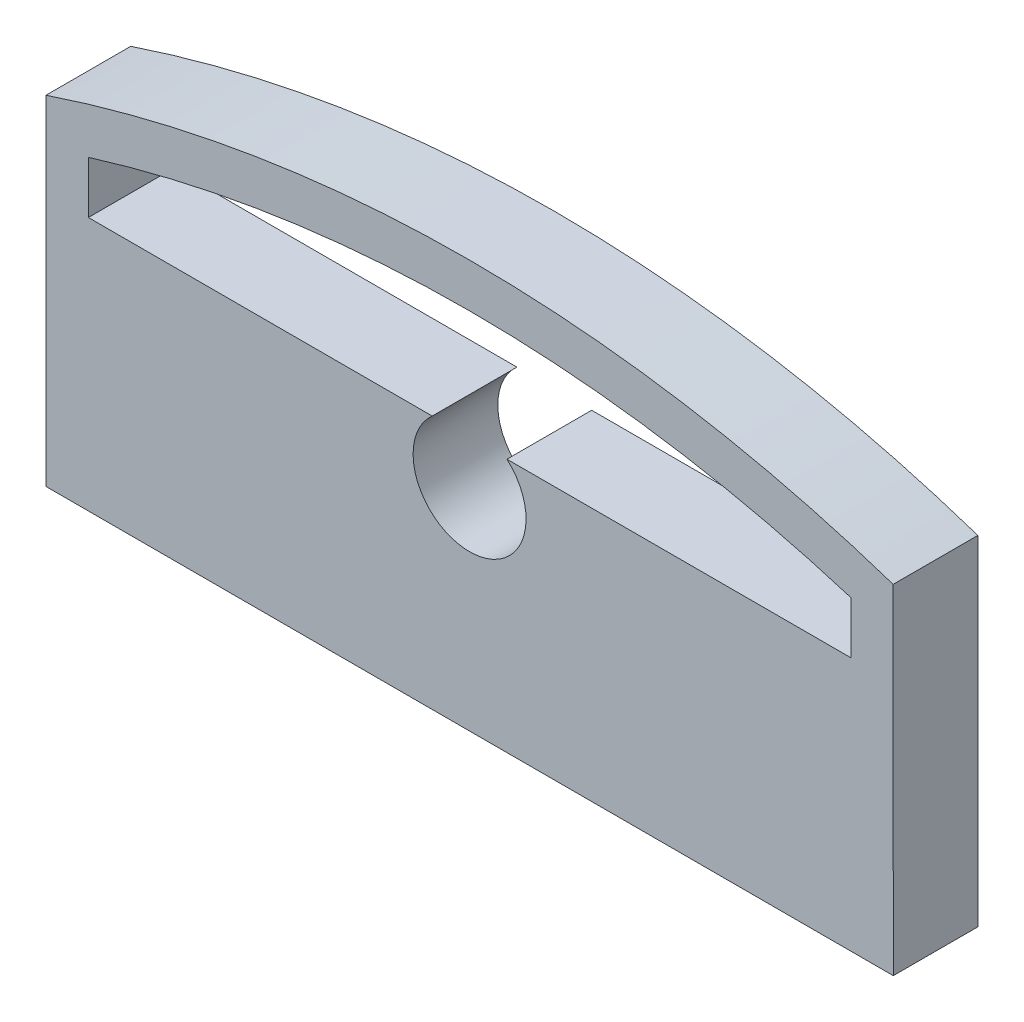
SolidWorks part; units mm, degrees
ref_plane "Front Plane" through (0, 0, 0) normal (0, 0, 1) x (1, 0, 0)
ref_plane "Top Plane" through (0, 0, 0) normal (0, 1, 0) x (1, 0, 0)
ref_plane "Right Plane" through (0, 0, 0) normal (1, 0, 0) x (0, 0, -1)
sketch "Sketch2" plane through (0, 0, 0) normal (0, 0, 1) x (1, 0, 0)
  circle A0 centre (0, 0) radius 95
  circle A1 centre (0, 0) radius 75
  dimension "D1" = 190
  dimension "D2" = 150
  dimension "D3" = 20
extrude "Boss-Extrude1" add sketch "Sketch2" along normal blind 5
sketch "Sketch3" plane through (0, 0, 0) normal (0, 0, 1) x (1, 0, 0)
  circle A0 centre (0, 0) radius 87
  circle A1 centre (0, 0) radius 95 construction
  circle A2 centre (0, 0) radius 84
  dimension "D1" = 8
  dimension "D2" = 3
extrude "Boss-Extrude2" add sketch "Sketch3" along normal blind 10
sketch "Sketch4" plane through (0, 0, 5) normal (0, 0, 1) x (1, 0, 0)
  circle A0 centre (0, 0) radius 75
  circle A1 centre (0, 0) radius 78
  dimension "D1" = 3
extrude "Boss-Extrude3" add sketch "Sketch4" along normal blind 70
sketch "Sketch5" plane through (0, 0, 0) normal (0, 0, 1) x (1, 0, 0)
  line L0 (0, 102.8311) -> (0, -104.5953) construction
  line L1 (-104.5953, 0) -> (100.8148, -2.2683) construction
ref_plane "Plane1" through (10, 0, 0) normal (1, 0, 0) x (0, 0, -1)
sketch "Sketch6" plane through (10, 0, 0) normal (1, 0, 0) x (0, 0, -1)
  line L1 (-45, 46) -> (-35, 46)
  line L2 (-45, 46) -> (-45, 34)
  line L3 (-45, 34) -> (-35, 34)
  line L4 (-35, 46) -> (-35, 34)
  line L5 (-45, 46) -> (-35, 34) construction
  line L6 (-45, 34) -> (-35, 46) construction
  point P0 (-40, 40)
  dimension "D1" = 10
  dimension "D2" = 12
extrude "Cut-Extrude3" cut sketch "Sketch6" against normal through all both and the other way through all
sketch "Sketch7" plane through (10, 0, 0) normal (1, 0, 0) x (0, 0, -1)
  line L1 (-45, -34) -> (-35, -34)
  line L2 (-45, -34) -> (-45, -46)
  line L3 (-45, -46) -> (-35, -46)
  line L4 (-35, -34) -> (-35, -46)
  line L5 (-45, -34) -> (-35, -46) construction
  line L6 (-45, -46) -> (-35, -34) construction
  point P0 (-40, -40)
  dimension "D1" = 10
  dimension "D2" = 12
extrude "Cut-Extrude4" cut sketch "Sketch7" against normal through all both and the other way through all
ref_plane "Plane2" through (0, 0, -10) normal (0, 0, -1) x (-1, 0, 0)
sketch "Sketch8" plane through (0, 0, -10) normal (0, 0, -1) x (-1, 0, 0)
  line L0 (0, 75) -> (-30, 75)
  line L1 (0, 102.8311) -> (0, -104.5953) construction
  line L2 (-30, 75) -> (-30, 96)
  line L3 (0, 75) -> (30, 75)
  line L4 (30, 75) -> (30, 96)
  circle A0 centre (0, 0) radius 75 construction
  arc A1 (-30, 96) -> (30, 96) centre (0, 6.4144) cw
extrude "Boss-Extrude4" add sketch "Sketch8" along normal blind 15 separate body
fillet "Fillet1" radius 20 1 edges at (0, 100.8897, -25)
shell "Shell1" thickness 3
sketch "Sketch9" plane through (10, 0, 0) normal (1, 0, 0) x (0, 0, -1)
  line L1 (-79.9983, 113.5266) -> (5.6569, 113.5266)
  line L2 (-79.9983, 113.5266) -> (-79.9983, -118.6202)
  line L3 (-79.9983, -118.6202) -> (5.6569, -118.6202)
  line L4 (5.6569, 113.5266) -> (5.6569, -118.6202)
extrude "Cut-Extrude5" cut sketch "Sketch9" against normal through all both and the other way through all
sketch "Sketch10" plane through (10, 0, 0) normal (1, 0, 0) x (0, 0, -1)
  line L1 (10, 75) -> (13, 75)
  line L2 (10, 75) -> (10, 90)
  line L3 (10, 90) -> (13, 90)
  line L4 (13, 75) -> (13, 90)
  dimension "D1" = 15
  dimension "D2" = 3
extrude "Boss-Extrude6" add sketch "Sketch10" along normal up to surface (54 mm away) from surface at -37 up to face at (27, 84.0519, -14.6097) starting at face at (-27, 83.5967, -14.9481)
sketch "Sketch11" plane through (0, 75, 0) normal (0, -1, 0) x (1, 0, 0)
  circle A0 centre (0, -19.1524) radius 2.5
  circle A1 centre (-8, -19.1524) radius 2.5
  circle A2 centre (-16, -19.1524) radius 2.5
  circle A3 centre (-24, -19.1524) radius 2.5
  circle A4 centre (8, -19.1524) radius 2.5
  circle A5 centre (16, -19.1524) radius 2.5
  circle A6 centre (24, -19.1524) radius 2.5
  dimension "D1" = 5
  dimension "D2" = 4
  dimension "D3" = 4
extrude "Cut-Extrude6" cut sketch "Sketch11" against normal blind 3
sketch "Sketch12" plane through (0, 75, 0) normal (0, -1, 0) x (-1, 0, 0)
  line L0 (55, 10) -> (-55, 10) construction
  line L1 (30, 25) -> (-30.0091, 25)
  line L2 (30, 25) -> (30, 10)
  line L3 (30, 10) -> (-30.0091, 10)
  line L4 (-30.0091, 25) -> (-30.0091, 10)
  line L6 (26.6611, 13.75) -> (-26.5509, 13.75)
  line L7 (26.6611, 13.75) -> (26.6611, 21.75)
  line L8 (26.6611, 21.75) -> (-26.5509, 21.75)
  line L9 (-26.5509, 13.75) -> (-26.5509, 21.75)
  dimension "D1" = 15
  dimension "D2" = 60.0091
  dimension "D3" = 8
  dimension "D4" = 3.75
extrude "Boss-Extrude7" add sketch "Sketch12" along normal blind 3
sketch "Sketch13" plane through (0, 0, -10) normal (0, 0, 1) x (1, 0, 0)
  line L0 (0, 102.8311) -> (0, -104.5953) construction
  line L1 (30.0091, 72) -> (-30, 72) construction
  circle A0 centre (0, 87) radius 4
  dimension "D1" = 8
  dimension "D2" = 15
extrude "Cut-Extrude7" cut sketch "Sketch13" against normal blind 5
sketch "Sketch16" plane through (0, 75, 0) normal (0, -1, 0) x (-1, 0, 0)
  line L1 (26.6611, 13.75) -> (-26.5509, 13.75)
  line L2 (26.6611, 13.75) -> (26.6611, 21.75)
  line L3 (26.6611, 21.75) -> (-26.5509, 21.75)
  line L4 (-26.5509, 13.75) -> (-26.5509, 21.75)
extrude "Cut-Extrude15" cut sketch "Sketch16" against normal blind 3 and the other way through all contours L2 L3 L4 L1
sketch "Sketch18" plane through (0, 72, 0) normal (0, -1, 0) x (-1, 0, 0)
  line L0 (30, 25) -> (-30.0091, 25) construction
  line L1 (27.9909, 13) -> (-28.0091, 13)
  line L2 (27.9909, 13) -> (27.9909, 23)
  line L3 (27.9909, 23) -> (-28.0091, 23)
  line L4 (-28.0091, 13) -> (-28.0091, 23)
  dimension "D1" = 10
  dimension "D2" = 2
  dimension "D3" = 56
  dimension "D4" = 2
extrude "Cut-Extrude18" cut sketch "Sketch18" against normal blind 3 contours L1 L4 L3 L2
sketch "Sketch21" plane through (0, 75, 0) normal (0, -1, 0) x (1, 0, 0)
  line L0 (26.5509, -13.75) -> (-26.6611, -13.75) construction
  line L1 (-26.6609, -13.75) -> (26.5391, -13.75)
  line L2 (-26.6609, -13.75) -> (-26.6609, -13)
  line L3 (-26.6609, -13) -> (26.5391, -13)
  line L4 (26.5391, -13.75) -> (26.5391, -13)
  line L5 (-27.9909, -13) -> (28.0091, -13) construction
  line L6 (28.0091, -13) -> (28.0091, -23) construction
  dimension "D1" = 53.2
  dimension "D2" = 1.47
extrude "Cut-Extrude19" cut sketch "Sketch21" against normal blind 3
sketch "Sketch23" plane through (0, 0, -10) normal (0, 0, -1) x (-1, 0, 0)
  line L0 (30, 96) -> (30, 72)
  line L1 (30, 72) -> (-30.0091, 72)
  line L2 (-30.0091, 72) -> (-30, 96)
  line L3 (27, 90) -> (-27, 90)
  line L4 (-27, 90) -> (-27, 93.6919)
  line L5 (27, 93.6919) -> (27, 90)
  arc A0 (-30, 96) -> (30, 96) centre (0, 6.4144) cw
  arc A1 (-27, 93.6919) -> (27, 93.6919) centre (0, 6.4144) cw
extrude "Boss-Extrude9" add sketch "Sketch23" against normal blind 6 contours L0 L1 L2 A0 | L4 A1 L5 L3
sketch "Sketch26" plane through (0, 0, -4) normal (0, 0, 1) x (1, 0, 0)
  line L0 (0, 102.8311) -> (0, -104.5953) construction
  line L2 (-30, 72) -> (30.0091, 72) construction
  circle A0 centre (0, 87) radius 4
  dimension "D1" = 8
  dimension "D2" = 15
extrude "Cut-Extrude20" cut sketch "Sketch26" against normal blind 10
sketch "Sketch27" plane through (10, 0, 0) normal (1, 0, 0) x (0, 0, -1)
  line L1 (10, 70.2257) -> (26.5552, 70.2257)
  line L2 (10, 70.2257) -> (10, 104.4158)
  line L3 (10, 104.4158) -> (26.5552, 104.4158)
  line L4 (26.5552, 70.2257) -> (26.5552, 104.4158)
extrude "Cut-Extrude21" cut sketch "Sketch27" against normal through all both and the other way through all contours L3 L4 L1 L2
